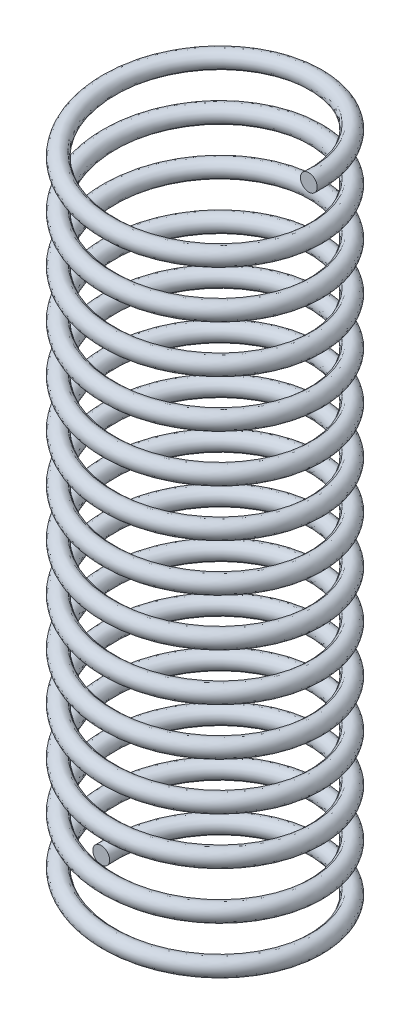
SolidWorks part; units mm, degrees
material "Alloy Steel"
ref_plane "Front Plane" through (0, 0, 0) normal (0, 0, 1) x (1, 0, 0)
ref_plane "Top Plane" through (0, 0, 0) normal (0, 1, 0) x (1, 0, 0)
ref_plane "Right Plane" through (0, 0, 0) normal (1, 0, 0) x (0, 0, -1)
sketch "Sketch1" plane through (0, 0, 0) normal (0, 0, 1) x (1, 0, 0)
  circle A0 centre (-7.0485, 0) radius 0.5715
  dimension "D1" = 7.0485
  dimension "D2" = 1.143
sketch "Sketch2" plane through (0, 0, 0) normal (0, 1, 0) x (1, 0, 0)
  circle A0 centre (0, 0) radius 7.0485
curve "Helix/Spiral1" pitch 3.2144 height 46.609 turns 14.5
sweep "Sweep1" add profiles "Sketch1" path "Helix/Spiral1"
